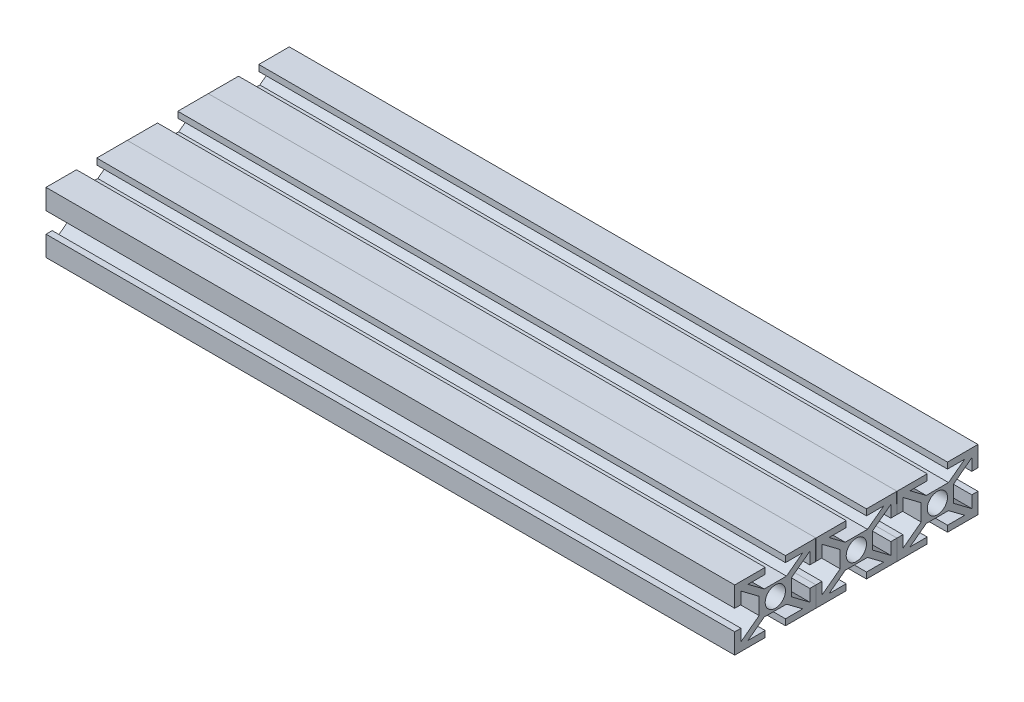
SolidWorks part; units mm, degrees
ref_plane "Front Plane" through (0, 0, 0) normal (0, 0, 1) x (1, 0, 0)
ref_plane "Top Plane" through (0, 0, 0) normal (0, 1, 0) x (1, 0, 0)
ref_plane "Right Plane" through (0, 0, 0) normal (1, 0, 0) x (0, 0, -1)
sketch "Sketch1" plane through (0, 0, 0) normal (1, 0, 0) x (0, 0, -1)
  line L0 (-17, 10.875) -> (-8, 4.125)
  line L5 (-20.0409, -15.0307) -> (20.0409, 15.0307) construction
  line L6 (-20.0594, 15.006) -> (20.0594, -15.006) construction
  line L7 (-13.5, 12) -> (-5.5, 6)
  line L8 (-13.5, -12) -> (-5.5, -6)
  line L9 (-17, -10.875) -> (-8, -4.125)
  line L10 (-28.9601, -0.0178) -> (34.699, 0.0214) construction
  line L11 (-0.0145, 23.6028) -> (0.0142, -23.0179) construction
  line L12 (-17, 10.875) -> (-17.0062, 5.0099)
  line L14 (-20.0471, 5.0099) -> (-17.0062, 5.0099)
  line L15 (-5.0148, 15.006) -> (-5.0148, 11.9938)
  line L16 (-20.0594, 15.006) -> (-5.0148, 15.006)
  line L17 (-20.0594, 15.006) -> (-20.0471, 5.0099)
  line L18 (20.0409, 15.0307) -> (20.0409, 5.0346)
  line L19 (20.0409, 5.0346) -> (17, 5.0308)
  line L20 (17, 10.875) -> (17, 5.0308)
  line L21 (20.0409, 15.0307) -> (4.9963, 15.0121)
  line L22 (4.9963, 15.0121) -> (5, 12)
  line L24 (17, -10.875) -> (17.0062, -5.0099)
  line L25 (20.0471, -5.0099) -> (17.0062, -5.0099)
  line L26 (20.0594, -15.006) -> (20.0471, -5.0099)
  line L27 (13.5, -12) -> (5.0148, -11.9938)
  line L28 (5.0148, -15.006) -> (5.0148, -11.9938)
  line L29 (20.0594, -15.006) -> (5.0148, -15.006)
  line L30 (-20.0409, -15.0307) -> (-20.0409, -5.0346)
  line L31 (-20.0409, -5.0346) -> (-17, -5.0308)
  line L32 (-17, -10.875) -> (-17, -5.0308)
  line L33 (-20.0409, -15.0307) -> (-4.9963, -15.0121)
  line L34 (-4.9963, -15.0121) -> (-5, -12)
  line L36 (8, -4.125) -> (17, -10.875)
  line L37 (-13.5, 12) -> (-5.0148, 11.9938)
  line L38 (13.5, 12) -> (5, 12)
  line L39 (-13.5, -12) -> (-5, -12)
  line L40 (5.5, -6) -> (13.5, -12)
  line L41 (5.5, 6) -> (13.5, 12)
  line L42 (8, 4.125) -> (17, 10.875)
  line L43 (-8, 5.9846) -> (-8, 6)
  line L44 (-5.5, -6) -> (5.5, -6)
  line L45 (-8, -4.125) -> (-8, 4.125)
  line L46 (-5.5, 6) -> (5.5, 6)
  line L47 (8, -6) -> (8, -5.9846)
  line L48 (-8, -6) -> (8, 6) construction
  line L49 (-8, 6) -> (8, -6) construction
  line L50 (8, -4.125) -> (8, 4.125)
  line L51 (26.5, 12) -> (34.5, 6)
  line L52 (34.5, 6) -> (45.5, 6)
  line L53 (45.5, 6) -> (53.5, 12)
  line L54 (53.5, 12) -> (45, 12)
  line L55 (44.9963, 15.0121) -> (45, 12)
  line L56 (60.0409, 15.0307) -> (44.9963, 15.0121)
  line L57 (60.0409, 15.0307) -> (60.0409, 5.0346)
  line L58 (60.0409, 5.0346) -> (57, 5.0308)
  line L59 (57, 10.875) -> (57, 5.0308)
  line L60 (48, 4.125) -> (57, 10.875)
  line L61 (48, -4.125) -> (48, 4.125)
  line L62 (48, -4.125) -> (57, -10.875)
  line L63 (57, -10.875) -> (57.0062, -5.0099)
  line L64 (60.0471, -5.0099) -> (57.0062, -5.0099)
  line L65 (60.0594, -15.006) -> (60.0471, -5.0099)
  line L66 (60.0594, -15.006) -> (45.0148, -15.006)
  line L67 (45.0148, -15.006) -> (45.0148, -11.9938)
  line L68 (53.5, -12) -> (45.0148, -11.9938)
  line L69 (45.5, -6) -> (53.5, -12)
  line L70 (34.5, -6) -> (45.5, -6)
  line L71 (26.5, -12) -> (34.5, -6)
  line L72 (26.5, -12) -> (35, -12)
  line L73 (35.0037, -15.0121) -> (35, -12)
  line L74 (19.9591, -15.0307) -> (35.0037, -15.0121)
  line L75 (19.9591, -15.0307) -> (19.9591, -5.0346)
  line L76 (19.9591, -5.0346) -> (23, -5.0308)
  line L77 (23, -10.875) -> (23, -5.0308)
  line L78 (23, -10.875) -> (32, -4.125)
  line L79 (32, -4.125) -> (32, 4.125)
  line L80 (23, 10.875) -> (32, 4.125)
  line L81 (23, 10.875) -> (22.9938, 5.0099)
  line L82 (19.9529, 5.0099) -> (22.9938, 5.0099)
  line L83 (19.9406, 15.006) -> (19.9529, 5.0099)
  line L84 (19.9406, 15.006) -> (34.9852, 15.006)
  line L85 (34.9852, 15.006) -> (34.9852, 11.9938)
  line L86 (26.5, 12) -> (34.9852, 11.9938)
  line L87 (66.5, 12) -> (74.5, 6)
  line L88 (74.5, 6) -> (85.5, 6)
  line L89 (85.5, 6) -> (93.5, 12)
  line L90 (93.5, 12) -> (85, 12)
  line L91 (84.9963, 15.0121) -> (85, 12)
  line L92 (100.0409, 15.0307) -> (84.9963, 15.0121)
  line L93 (100.0409, 15.0307) -> (100.0409, 5.0346)
  line L94 (100.0409, 5.0346) -> (97, 5.0308)
  line L95 (97, 10.875) -> (97, 5.0308)
  line L96 (88, 4.125) -> (97, 10.875)
  line L97 (88, -4.125) -> (88, 4.125)
  line L98 (88, -4.125) -> (97, -10.875)
  line L99 (97, -10.875) -> (97.0062, -5.0099)
  line L100 (100.0471, -5.0099) -> (97.0062, -5.0099)
  line L101 (100.0594, -15.006) -> (100.0471, -5.0099)
  line L102 (100.0594, -15.006) -> (85.0148, -15.006)
  line L103 (85.0148, -15.006) -> (85.0148, -11.9938)
  line L104 (93.5, -12) -> (85.0148, -11.9938)
  line L105 (85.5, -6) -> (93.5, -12)
  line L106 (74.5, -6) -> (85.5, -6)
  line L107 (66.5, -12) -> (74.5, -6)
  line L108 (66.5, -12) -> (75, -12)
  line L109 (75.0037, -15.0121) -> (75, -12)
  line L110 (59.9591, -15.0307) -> (75.0037, -15.0121)
  line L111 (59.9591, -15.0307) -> (59.9591, -5.0346)
  line L112 (59.9591, -5.0346) -> (63, -5.0308)
  line L113 (63, -10.875) -> (63, -5.0308)
  line L114 (63, -10.875) -> (72, -4.125)
  line L115 (72, -4.125) -> (72, 4.125)
  line L116 (63, 10.875) -> (72, 4.125)
  line L117 (63, 10.875) -> (62.9938, 5.0099)
  line L118 (59.9529, 5.0099) -> (62.9938, 5.0099)
  line L119 (59.9406, 15.006) -> (59.9529, 5.0099)
  line L120 (59.9406, 15.006) -> (74.9852, 15.006)
  line L121 (74.9852, 15.006) -> (74.9852, 11.9938)
  line L122 (66.5, 12) -> (74.9852, 11.9938)
  line L123 (-13.5, 12) -> (26.5, 12) construction
  circle A0 centre (0, 0) radius 5
  circle A1 centre (40, 0) radius 5
  circle A2 centre (80, 0) radius 5
  point P0 (0, 0)
  dimension "D1" = 40
  dimension "D2" = 3
extrude "Boss-Extrude1" add sketch "Sketch1" along normal blind 340
